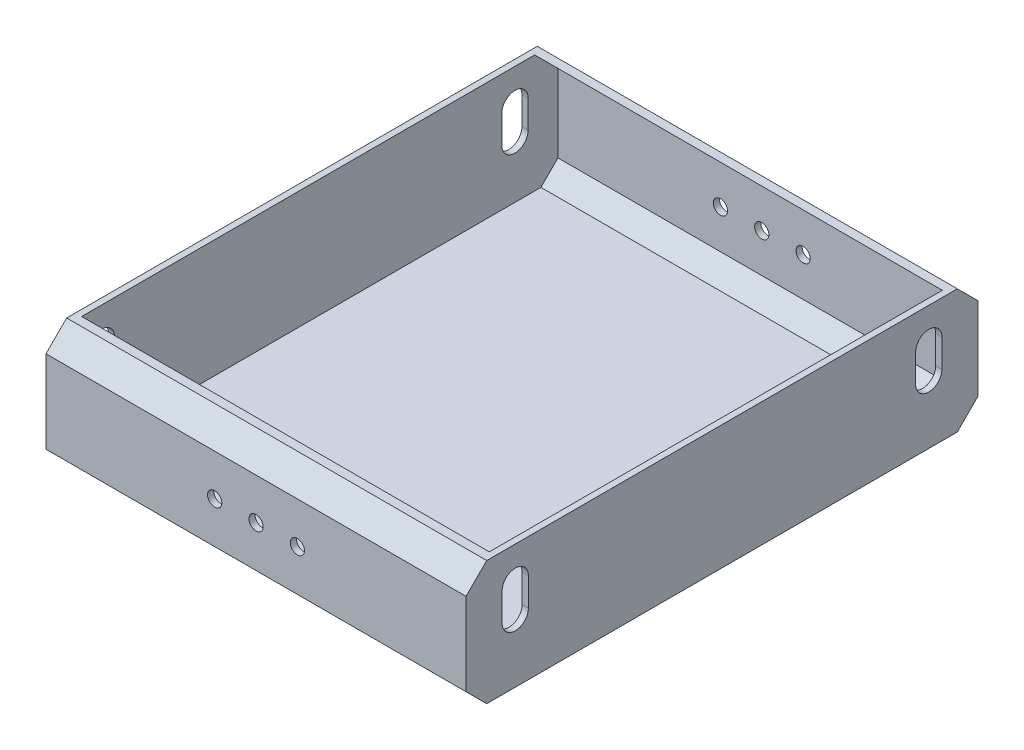
SolidWorks part; units mm, degrees
ref_plane "Front Plane" through (0, 0, 0) normal (0, 0, 1) x (1, 0, 0)
ref_plane "Top Plane" through (0, 0, 0) normal (0, 1, 0) x (1, 0, 0)
ref_plane "Right Plane" through (0, 0, 0) normal (1, 0, 0) x (0, 0, -1)
sketch "Sketch1" plane through (0, 0, 0) normal (0, 1, 0) x (1, 0, 0)
  line L1 (-101.6, 123.825) -> (101.6, 123.825)
  line L2 (-101.6, 123.825) -> (-101.6, -123.825)
  line L3 (-101.6, -123.825) -> (101.6, -123.825)
  line L4 (101.6, 123.825) -> (101.6, -123.825)
  line L5 (-101.6, 123.825) -> (101.6, -123.825) construction
  line L6 (-101.6, -123.825) -> (101.6, 123.825) construction
  point P0 (0, 0)
  dimension "D1" = 203.2
  dimension "D2" = 247.65
extrude "Boss-Extrude1" add sketch "Sketch1" along normal blind 60
chamfer "Chamfer1" distance 10 angle 45 4 edges at (0, 0, 123.825) (0, 60, 123.825) (0, 0, -123.825) (0, 60, -123.825)
shell "Shell3" thickness 3
sketch "Sketch2" plane through (-101.6, 0, 0) normal (-1, 0, 0) x (0, 0, 1)
  line L0 (-100.025, 43.55) -> (-100.025, 30) construction
  line L1 (-93.675, 43.55) -> (-93.675, 30)
  line L2 (-106.375, 43.55) -> (-106.375, 30)
  line L3 (-123.825, 50) -> (-123.825, 10) construction
  arc A0 (-93.675, 43.55) -> (-106.375, 43.55) centre (-100.025, 43.55) ccw
  arc A1 (-106.375, 30) -> (-93.675, 30) centre (-100.025, 30) ccw
  point P2 (-100.025, 36.775)
  point P7 (-87.0093, 25.2293)
  point P8 (-86.9313, 31.675)
  point P9 (0, 0)
  point P12 (-123.825, 30)
  dimension "D1" = 12.7
  dimension "D2" = 13.55
  dimension "D3" = 23.8
extrude "Cut-Extrude1" cut sketch "Sketch2" against normal up to next
mirror "Mirror1" about plane through (0, 0, 0) normal (0, 0, 1) of "Cut-Extrude1" second plane through (0, 0, 0) second plane normal (1, 0, 0)
sketch "Sketch3" plane through (0, 0, -123.825) normal (0, 0, -1) x (-1, 0, 0)
  line L0 (-101.6, 30) -> (101.6, 30) construction
  line L1 (-101.6, 50) -> (-101.6, 10) construction
  line L2 (101.6, 50) -> (101.6, 10) construction
  circle A0 centre (0, 30) radius 3.45
  circle A1 centre (20, 30) radius 3.45
  circle A2 centre (-20, 30) radius 3.45
  point P16 (0, 30)
  dimension "D1" = 6.9
  dimension "D2" = 20
  dimension "D3" = 20
extrude "Cut-Extrude2" cut sketch "Sketch3" against normal up to next
mirror "Mirror2" about plane through (0, 0, 0) normal (0, 0, 1) of "Cut-Extrude2"
